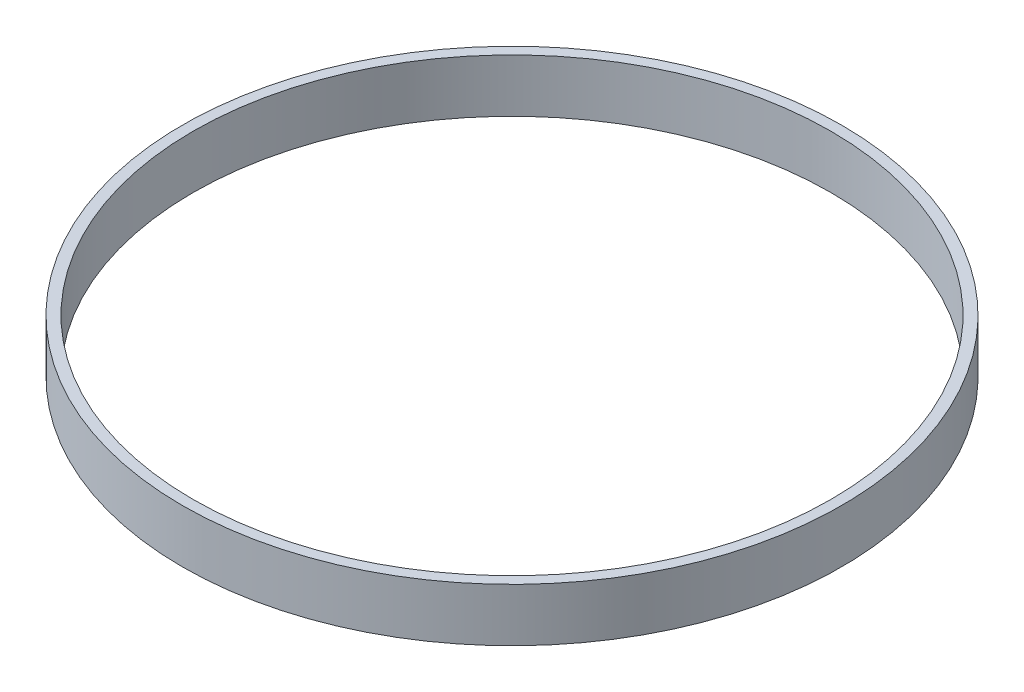
SolidWorks part; units mm, degrees
ref_plane "Front Plane" through (0, 0, 0) normal (0, 0, 1) x (1, 0, 0)
ref_plane "Top Plane" through (0, 0, 0) normal (0, 1, 0) x (1, 0, 0)
ref_plane "Right Plane" through (0, 0, 0) normal (1, 0, 0) x (0, 0, -1)
sketch "Sketch1" plane through (0, 0, 0) normal (0, 1, 0) x (1, 0, 0)
  circle A0 centre (0, 0) radius 15
  circle A1 centre (0, 0) radius 15.5
  dimension "D1" = 30
  dimension "D2" = 0.5
extrude "Boss-Extrude1" add sketch "Sketch1" along normal blind 2.5
scale "Echelle1" bodies to scale 101 scale about centroid uniform scaling yes scale factor 0.5
